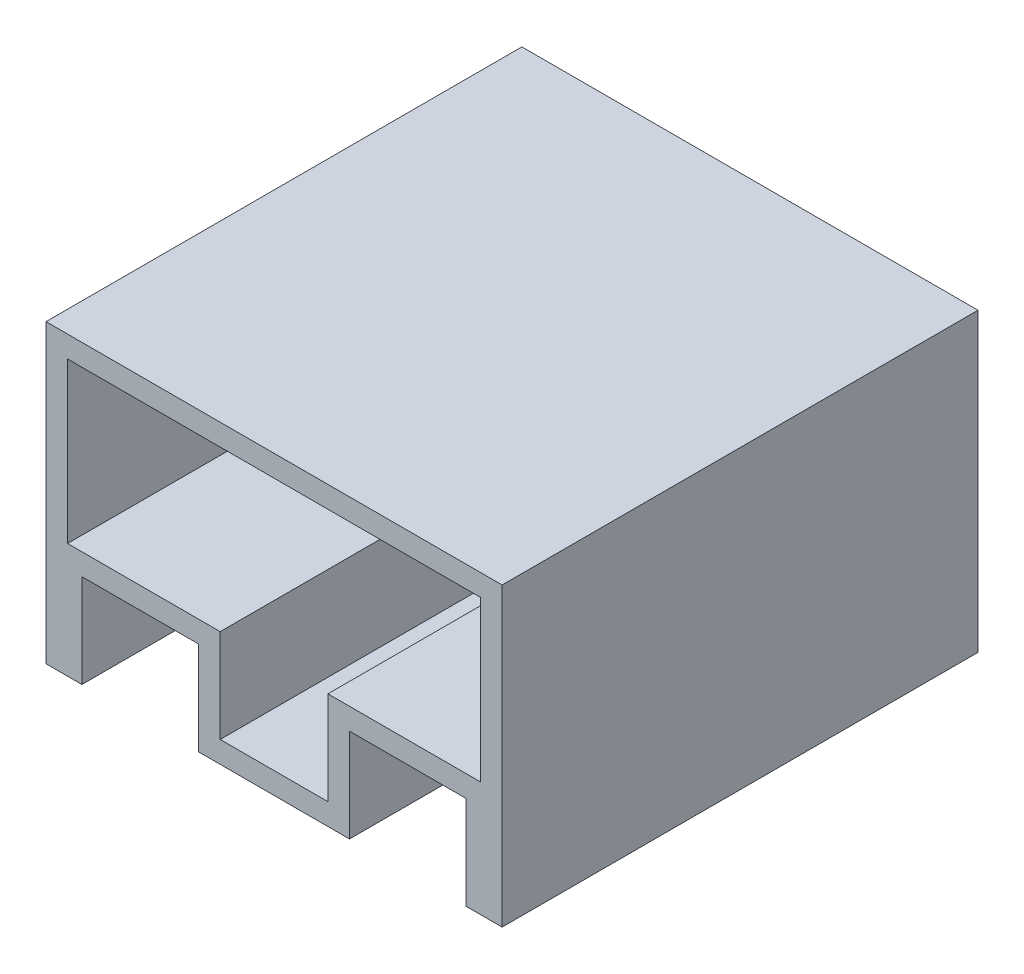
SolidWorks part; units mm, degrees
ref_plane "前视基准面" through (0, 0, 0) normal (0, 0, 1) x (1, 0, 0)
ref_plane "上视基准面" through (0, 0, 0) normal (0, 1, 0) x (1, 0, 0)
ref_plane "右视基准面" through (0, 0, 0) normal (1, 0, 0) x (0, 0, -1)
sketch "草图1" plane through (0, 0, 0) normal (0, 0, 1) x (1, 0, 0)
  line L0 (-1.2, 1.2) -> (24.2, 1.2)
  line L1 (0, 0) -> (23, 0)
  line L2 (0, 0) -> (0, -8.9)
  line L3 (0, -8.9) -> (8.5, -8.9)
  line L4 (23, 0) -> (23, -8.9)
  line L5 (24.2, 1.2) -> (24.2, -10.1)
  line L6 (-1.2, -10.1) -> (7.3, -10.1)
  line L7 (-1.2, 1.2) -> (-1.2, -10.1)
  line L8 (11.5, -8.9) -> (11.5, -15.5071) construction
  line L9 (8.5, -8.9) -> (8.5, -14.1)
  line L10 (8.5, -14.1) -> (14.5, -14.1)
  line L11 (14.5, -14.1) -> (14.5, -8.9)
  line L12 (7.3, -10.1) -> (7.3, -15.3)
  line L13 (7.3, -15.3) -> (15.7, -15.3)
  line L14 (15.7, -15.3) -> (15.7, -10.1)
  line L15 (15.7, -10.1) -> (24.2, -10.1)
  line L16 (14.5, -8.9) -> (23, -8.9)
  line L17 (-1.2, -10.1) -> (24.2, -10.1) construction
  line L19 (0, -8.9) -> (23, -8.9) construction
  line L20 (7.3, -8.9) -> (7.3, -15.3) construction
  line L21 (15.7, -15.3) -> (15.7, -8.9) construction
  dimension "D1" = 23
  dimension "D2" = 8.9
  dimension "D4" = 6
  dimension "D5" = 5.2
  dimension "D3" = 1.2
  dimension "D6" = 1.2
extrude "凸台-拉伸1" add sketch "草图1" along normal blind 26.5
sketch "草图2" plane through (0, -10.1, 0) normal (0, -1, 0) x (1, 0, 0)
  line L0 (-1.2, 0) -> (7.3, 0) construction
  line L1 (-1.2, 26.5) -> (0.8, 26.5)
  line L2 (-1.2, 26.5) -> (-1.2, 0)
  line L3 (-1.2, 0) -> (0.8, 0)
  line L4 (0.8, 26.5) -> (0.8, 0)
  line L5 (15.7, 0) -> (24.2, 0) construction
  line L6 (24.2, 26.5) -> (22.2, 26.5)
  line L7 (24.2, 26.5) -> (24.2, 0)
  line L8 (24.2, 0) -> (22.2, 0)
  line L9 (22.2, 26.5) -> (22.2, 0)
  dimension "D1" = 2
  dimension "D2" = 2
extrude "凸台-拉伸2" add sketch "草图2" along normal up to vertex (5.2 mm away) up to point (7.3, -15.3, 26.5)
